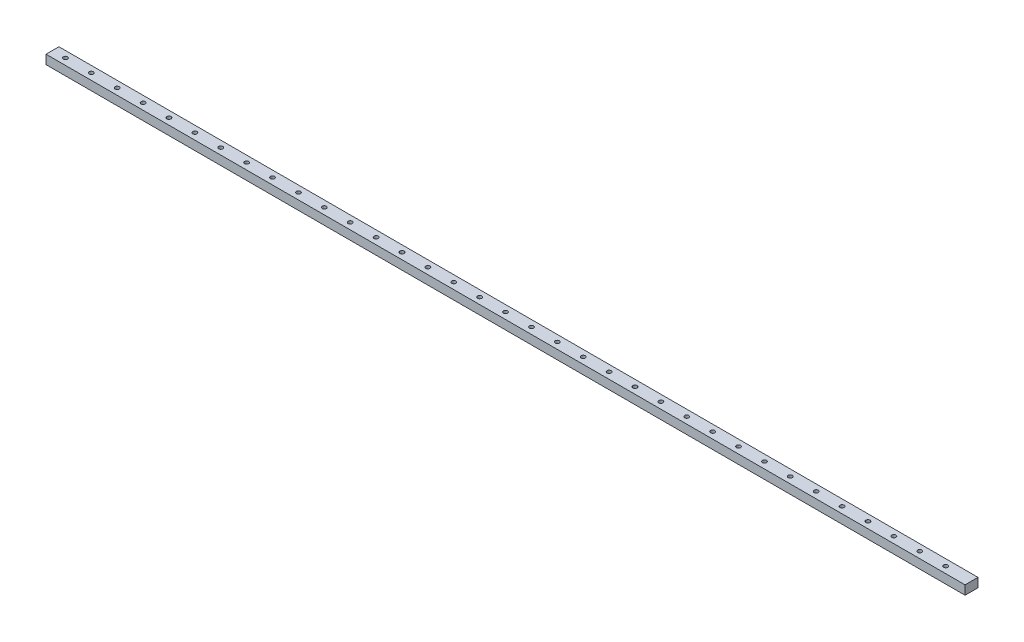
SolidWorks part; units mm, degrees
ref_plane "前视基准面" through (0, 0, 0) normal (0, 0, 1) x (1, 0, 0)
ref_plane "上视基准面" through (0, 0, 0) normal (0, 1, 0) x (1, 0, 0)
ref_plane "右视基准面" through (0, 0, 0) normal (1, 0, 0) x (0, 0, -1)
other "Configuration Table"
sketch "草图1" plane through (0, 0, 0) normal (0, 1, 0) x (1, 0, 0)
  line L0 (-345, 0) -> (-355, 0) construction
  line L1 (-355, -5) -> (355, -5)
  line L2 (-355, -5) -> (-355, 5)
  line L3 (-355, 5) -> (355, 5)
  line L4 (355, -5) -> (355, 5)
  line L5 (-355, -5) -> (355, 5) construction
  line L6 (-355, 5) -> (355, -5) construction
  circle A0 centre (-345, 0) radius 1.6
  circle A1 centre (-325, 0) radius 1.6
  circle A2 centre (-305, 0) radius 1.6
  circle A3 centre (-285, 0) radius 1.6
  circle A4 centre (-265, 0) radius 1.6
  circle A5 centre (-245, 0) radius 1.6
  circle A6 centre (-225, 0) radius 1.6
  circle A7 centre (-205, 0) radius 1.6
  circle A8 centre (-185, 0) radius 1.6
  circle A9 centre (-165, 0) radius 1.6
  circle A10 centre (-145, 0) radius 1.6
  circle A11 centre (-125, 0) radius 1.6
  circle A12 centre (-105, 0) radius 1.6
  circle A13 centre (-85, 0) radius 1.6
  circle A14 centre (-65, 0) radius 1.6
  circle A15 centre (-45, 0) radius 1.6
  circle A16 centre (-25, 0) radius 1.6
  circle A17 centre (-5, 0) radius 1.6
  circle A18 centre (15, 0) radius 1.6
  circle A19 centre (35, 0) radius 1.6
  circle A20 centre (55, 0) radius 1.6
  circle A21 centre (75, 0) radius 1.6
  circle A22 centre (95, 0) radius 1.6
  circle A23 centre (115, 0) radius 1.6
  circle A24 centre (135, 0) radius 1.6
  circle A25 centre (155, 0) radius 1.6
  circle A26 centre (175, 0) radius 1.6
  circle A27 centre (195, 0) radius 1.6
  circle A28 centre (215, 0) radius 1.6
  circle A29 centre (235, 0) radius 1.6
  circle A30 centre (255, 0) radius 1.6
  circle A31 centre (275, 0) radius 1.6
  circle A32 centre (295, 0) radius 1.6
  circle A33 centre (315, 0) radius 1.6
  circle A34 centre (335, 0) radius 1.6
  point P0 (0, 0)
  dimension "D3" = 3.2
  dimension "D1" = 710
  dimension "D2" = 10
  dimension "D4" = 10
  dimension "D6" = 20
  dimension "D5" = 35
extrude "凸台-拉伸1" add sketch "草图1" along normal blind 7
